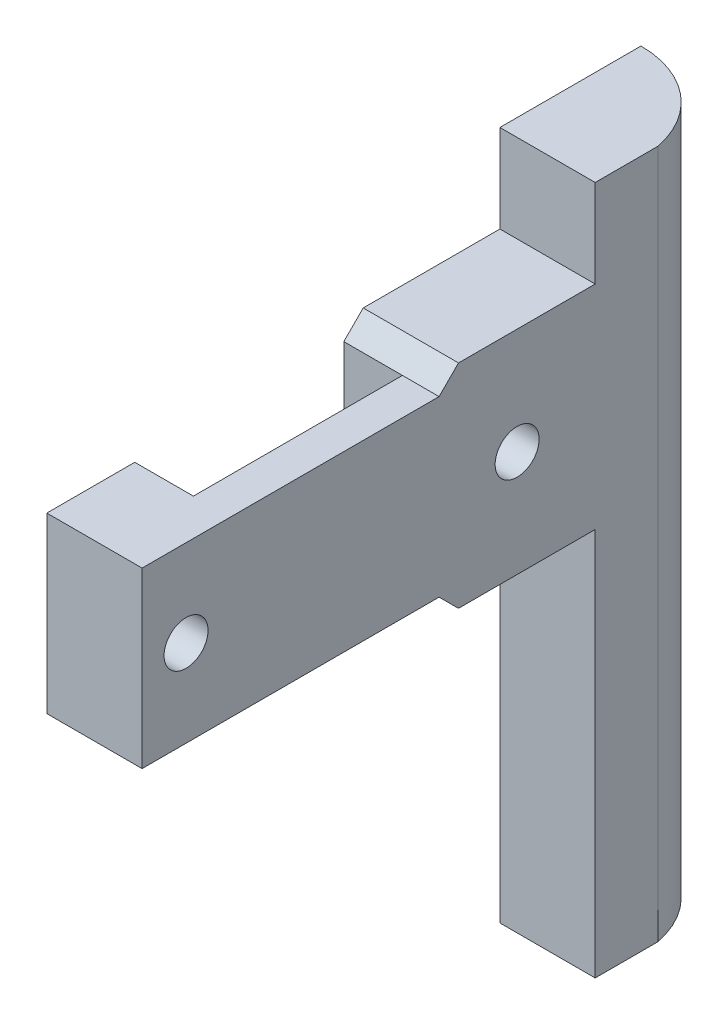
SolidWorks part; units mm, degrees
material "ABS"
ref_plane "Front" through (0, 0, 0) normal (0, 0, 1) x (1, 0, 0)
ref_plane "Top" through (0, 0, 0) normal (0, 1, 0) x (1, 0, 0)
ref_plane "Right" through (0, 0, 0) normal (1, 0, 0) x (0, 0, -1)
sketch "Sketch1" plane through (0, 0, 0) normal (1, 0, 0) x (0, 0, -1)
  line L1 (10.65, 14.5) -> (-10.65, 14.5)
  line L2 (10.65, 14.5) -> (10.65, -14.5)
  line L3 (10.65, -14.5) -> (-10.65, -14.5)
  line L4 (-10.65, 14.5) -> (-10.65, -14.5)
  line L5 (10.65, 14.5) -> (-10.65, -14.5) construction
  line L6 (10.65, -14.5) -> (-10.65, 14.5) construction
  point P0 (0, 0)
  dimension "D1" = 21.3
  dimension "D2" = 29
extrude "Boss-Extrude1" add sketch "Sketch1" along normal blind 25.87
sketch "Sketch3" plane through (25.87, 0, 0) normal (1, 0, 0) x (0, 0, -1)
  line L0 (-7.9983, 14.5) -> (-10.65, 11.8483)
  line L1 (-10.65, 11.8483) -> (-10.65, 14.5)
  line L2 (-10.65, 14.5) -> (-7.9983, 14.5)
  line L3 (-12.9395, 0) -> (4.891, 0)
  line L4 (10.65, 14.5) -> (-10.65, 14.5) construction
  line L5 (-10.65, 14.5) -> (-10.65, -14.5) construction
  line L6 (-10.65, -11.8483) -> (-10.65, -14.5)
  line L7 (-7.9983, -14.5) -> (-10.65, -11.8483)
  line L8 (-10.65, -14.5) -> (-7.9983, -14.5)
  line M6 (-10.65, 14.5) -> (-10.65, -14.5)
  line M7 (-10.65, -14.5) -> (10.65, -14.5)
  dimension "D1" = 0
  dimension "D2" = 45
  dimension "D3" = 3.75
  dimension "D4" = 17.8305
  dimension "D5" = 14.5
  dimension "D6" = 2.2895
extrude "Cut-Extrude1" cut sketch "Sketch3" against normal through all contours L7 M7 M6 | L1 L2 L0
sketch "Sketch5" plane through (0, 0, 10.65) normal (0, 0, 1) x (1, 0, 0)
  line L0 (25.87, 11.8483) -> (25.87, -11.8483) construction
  line L1 (25.87, 11.8483) -> (20.87, 11.8483)
  line L2 (25.87, 11.8483) -> (25.87, -11.8517)
  line L3 (25.87, -11.8517) -> (20.87, -11.8517)
  line L4 (20.87, 11.8483) -> (20.87, -11.8517)
  line L5 (25.87, 11.8483) -> (20.87, -11.8517) construction
  line L6 (25.87, -11.8517) -> (20.87, 11.8483) construction
  line L7 (5, 11.8483) -> (0, 11.8483)
  line L8 (5, 11.8483) -> (5, -11.8517)
  line L9 (5, -11.8517) -> (0, -11.8517)
  line L10 (0, 11.8483) -> (0, -11.8517)
  line L11 (5, 11.8483) -> (0, -11.8517) construction
  line L12 (5, -11.8517) -> (0, 11.8483) construction
  line L13 (0, 11.8483) -> (25.87, 11.8483) construction
  line L14 (0, 11.8483) -> (0, -11.8483) construction
  point P0 (23.37, -0.0017)
  point P5 (2.5, -0.0017)
  dimension "D1" = 0
  dimension "D2" = 5
  dimension "D3" = 0
  dimension "D4" = 23.7
  dimension "D5" = 0
  dimension "D6" = 0
  dimension "D7" = 5
  dimension "D8" = 23.7
extrude "Boss-Extrude2" add sketch "Sketch5" along normal blind 33.52
sketch "Sketch6" plane through (20.87, 0, 0) normal (-1, 0, 0) x (0, 0, 1)
  line L0 (44.17, 11.8483) -> (10.65, 11.8483) construction
  line L1 (44.17, 11.8483) -> (39.17, 11.8483)
  line L2 (44.17, 11.8483) -> (44.17, -11.8517)
  line L3 (44.17, -11.8517) -> (39.17, -11.8517)
  line L4 (39.17, 11.8483) -> (39.17, -11.8517)
  line L5 (44.17, 11.8483) -> (39.17, -11.8517) construction
  line L6 (44.17, -11.8517) -> (39.17, 11.8483) construction
  line L7 (44.17, 11.8483) -> (44.17, -11.8517) construction
  point P0 (41.67, -0.0017)
  point P5 (41.67, 11.8483)
  dimension "D1" = 0
  dimension "D2" = 0
  dimension "D3" = 5
  dimension "D4" = 23.7
extrude "Boss-Extrude3" add sketch "Sketch6" along normal blind 15.9
sketch "Sketch7" plane through (0, 0, -10.65) normal (0, 0, -1) x (-1, 0, 0)
  line L0 (-25.87, 14.5) -> (0, 14.5) construction
  line L1 (0, 26.5) -> (-25.87, 26.5)
  line L2 (0, 26.5) -> (0, -67.5)
  line L3 (0, -67.5) -> (-25.87, -67.5)
  line L4 (-25.87, 26.5) -> (-25.87, -67.5)
  line L5 (0, 26.5) -> (-25.87, -67.5) construction
  line L6 (0, -67.5) -> (-25.87, 26.5) construction
  line L7 (-25.87, -14.5) -> (0, -14.5) construction
  line L8 (0, -14.5) -> (0, 14.5) construction
  line L9 (-25.87, -14.5) -> (-25.87, 14.5) construction
  point P0 (-12.935, -20.5)
  point P5 (-12.935, 26.5)
  dimension "D1" = 12
  dimension "D2" = 53
  dimension "D3" = 0
  dimension "D4" = 0
extrude "Boss-Extrude4" add sketch "Sketch7" along normal blind 20
sketch "Sketch9" plane through (0, -67.5, 0) normal (0, -1, 0) x (-1, 0, 0)
  line L0 (-25.87, 10.65) -> (0, 10.65) construction
  line L1 (-25.87, 30.65) -> (-25.87, 10.65) construction
  line L2 (0.38, 16.65) -> (-26.12, 16.65)
  line L3 (-26.12, 16.65) -> (-26.12, 30.65)
  line L4 (-26.12, 30.65) -> (0.38, 30.65)
  line L5 (0.38, 30.65) -> (0.38, 16.65)
  circle A0 centre (-12.87, 16.65) radius 13.25
  line M5 (0, 10.65) -> (0, 30.65)
  line M6 (0, 30.65) -> (-25.87, 30.65)
  dimension "D1" = 6
  dimension "D2" = 13
  dimension "D3" = 26.5
  dimension "D4" = 14
  dimension "D5" = 26.5
  dimension "D6" = 90
extrude "Cut-Extrude2" cut sketch "Sketch9" against normal through all contours A0 L3 M5 M6
sketch "Sketch10" plane through (0, 0, 44.17) normal (0, 0, 1) x (1, 0, 0)
  line L1 (25.87, 11.8483) -> (0, 11.8483)
  line L2 (25.87, 11.8483) -> (25.87, -11.8517)
  line L3 (25.87, -11.8517) -> (0, -11.8517)
  line L4 (0, 11.8483) -> (0, -11.8517)
  dimension "D1" = 25.87
  dimension "D2" = 23.7
extrude "Boss-Extrude5" add sketch "Sketch10" along normal blind 7
hole_wizard "Ø6.0mm Clearance Dowel Hole1" positions "Sketch11" profile "Sketch12" hole size "Ø6.0" standard "ANSI Metric" end condition through all
sketch "Sketch11" plane through (25.87, 0, 0) normal (1, 0, 0) x (0, 0, -1)
  line L1 (-51.17, -11.8517) -> (-51.17, 11.8483) construction
  line L3 (-51.17, 11.8483) -> (-10.65, 11.8483) construction
  point P0 (-45.17, 0)
  point P2 (0, 0)
  dimension "D1" = 11.8483
  dimension "D2" = 6
sketch "Sketch12" plane through (25.87, 0, 45.17) normal (0, 1, 0) x (0, 0, -1)
  line L0 (0, 0) -> (0, 25.87)
  line L1 (0, 25.87) -> (3, 25.87)
  line L2 (3, 25.87) -> (3, 0)
  line L5 (3, 0) -> (0, 0)
  line L11 (0, -6.35) -> (0, 107.95) construction
  dimension "Thru Hole Dia." = 6
  dimension "Thru Hole Depth" = 25.87
sketch "Sketch13" plane through (0, 0, 51.17) normal (0, 0, 1) x (1, 0, 0)
  line L0 (0, 11.8483) -> (0, -11.8517) construction
  line L1 (12.87, 69.9983) -> (-12.87, 69.9983)
  line L2 (12.87, 69.9983) -> (12.87, -70.0017)
  line L3 (12.87, -70.0017) -> (-12.87, -70.0017)
  line L4 (-12.87, 69.9983) -> (-12.87, -70.0017)
  line L5 (12.87, 69.9983) -> (-12.87, -70.0017) construction
  line L6 (12.87, -70.0017) -> (-12.87, 69.9983) construction
  point P0 (0, -0.0017)
  dimension "D1" = 70
  dimension "D2" = 12.87
extrude "Cut-Extrude3" cut sketch "Sketch13" against normal through all
